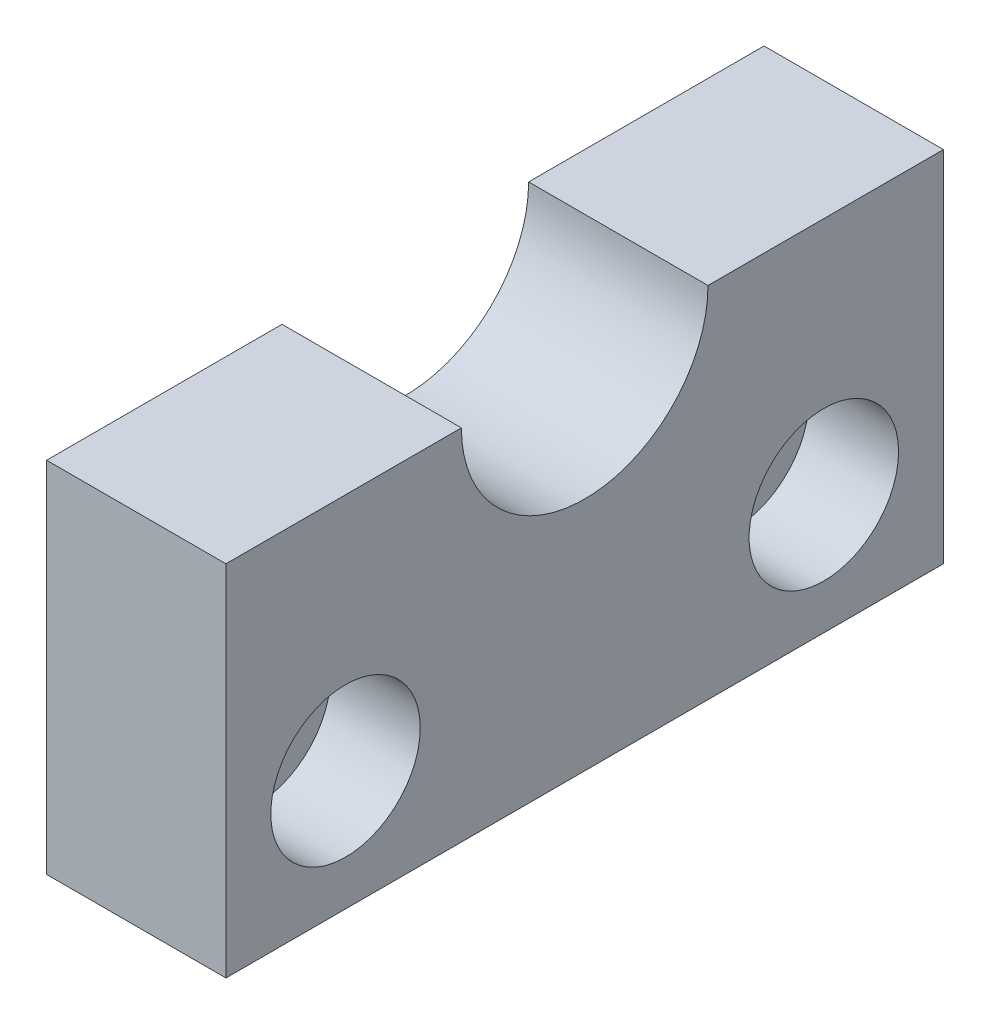
SolidWorks part; units mm, degrees
material "6061-T6 (SS)"
ref_plane "Front" through (0, 0, 0) normal (0, 0, 1) x (1, 0, 0)
ref_plane "Top" through (0, 0, 0) normal (0, 1, 0) x (1, 0, 0)
ref_plane "Right" through (0, 0, 0) normal (1, 0, 0) x (0, 0, -1)
sketch "Sketch1" plane through (0, 0, 0) normal (1, 0, 0) x (0, 0, -1)
  line L1 (0, 0) -> (76.2, 0)
  line L2 (0, 0) -> (0, 76.2)
  line L3 (0, 76.2) -> (76.2, 76.2)
  line L4 (76.2, 0) -> (76.2, 76.2)
  dimension "D1" = 76.2
  dimension "D2" = 76.2
extrude "Boss-Extrude1" add sketch "Sketch1" along normal blind 19.05
sketch "Sketch2" plane through (19.05, 0, 0) normal (1, 0, 0) x (0, 0, -1)
  line L0 (0, 76.2) -> (0, 0) construction
  line L1 (0, 0) -> (76.2, 0) construction
  circle A0 centre (38.1, 38.1) radius 13.0969
  dimension "D1" = 38.1
  dimension "D3" = 26.1937
  dimension "D2" = 38.1
extrude "Cut-Extrude1" cut sketch "Sketch2" against normal through all
hole_wizard "CBORE for 3/8 Socket Head Cap Screw1" positions "Sketch3" profile "Sketch4" counterbore size "3/8" standard "ANSI Inch" end condition through all
sketch "Sketch3" plane through (19.05, 0, 0) normal (1, 0, 0) x (0, 0, -1)
  line L0 (0, 76.2) -> (0, 0) construction
  line L1 (0, 0) -> (76.2, 0) construction
  point P0 (12.7, 12.7)
  point P2 (63.5, 12.7)
  dimension "D1" = 12.7
  dimension "D2" = 63.5
  dimension "D3" = 12.7
  dimension "D4" = 12.7
sketch "Sketch4" plane through (19.05, 12.7, -12.7) normal (0, 1, 0) x (0, 0, -1)
  line L0 (0, 0) -> (0, 19.05)
  line L1 (0, 19.05) -> (4.9022, 19.05)
  line L3 (4.9022, 19.05) -> (4.9022, 9.525)
  line L4 (4.9022, 9.525) -> (7.9375, 9.525)
  line L5 (7.9375, 9.525) -> (7.9375, 0)
  line L7 (7.9375, 0) -> (0, 0)
  line L11 (0, -6.35) -> (0, 107.95) construction
  dimension "Thru Hole Dia." = 9.8044
  dimension "Thru Hole Depth" = 19.05
  dimension "C'Bore Dia." = 15.875
  dimension "C'Bore Depth" = 9.525
sketch "Sketch5" plane through (19.05, 0, 0) normal (1, 0, 0) x (0, 0, -1)
  line L0 (0, 76.2) -> (0, 0) construction
  line L1 (0, 38.1) -> (76.2, 38.1)
  line L2 (0, 38.1) -> (0, 76.2)
  line L3 (0, 76.2) -> (76.2, 76.2)
  line L4 (76.2, 38.1) -> (76.2, 76.2)
  line L5 (76.2, 0) -> (76.2, 76.2) construction
  line L6 (76.2, 76.2) -> (0, 76.2) construction
  dimension "D1" = 0
  dimension "D2" = 0
  dimension "D3" = 0
  dimension "D4" = 38.1
extrude "Cut-Extrude2" cut sketch "Sketch5" against normal through all
